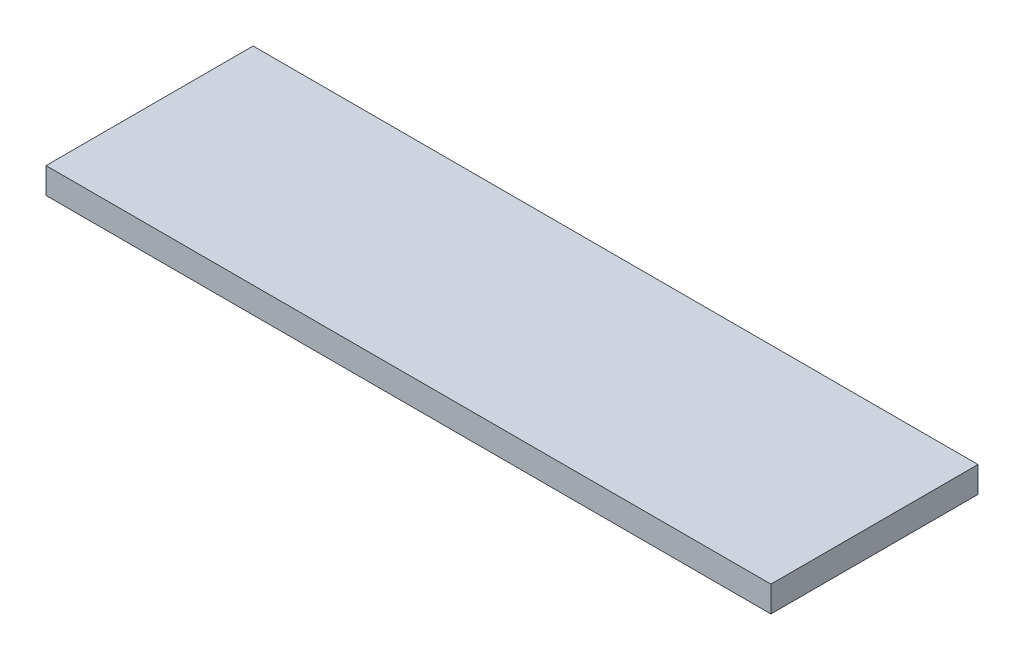
SolidWorks part; units mm, degrees
ref_plane "Front Plane" through (0, 0, 0) normal (0, 0, 1) x (1, 0, 0)
ref_plane "Top Plane" through (0, 0, 0) normal (0, 1, 0) x (1, 0, 0)
ref_plane "Right Plane" through (0, 0, 0) normal (1, 0, 0) x (0, 0, -1)
sketch "Sketch1" plane through (0, 0, 0) normal (0, 1, 0) x (1, 0, 0)
  line L1 (0, 0) -> (88.9, 0)
  line L2 (0, 0) -> (0, 25.4)
  line L3 (0, 25.4) -> (88.9, 25.4)
  line L4 (88.9, 0) -> (88.9, 25.4)
  dimension "D1" = 25.4
  dimension "D2" = 88.9
extrude "Boss-Extrude1" add sketch "Sketch1" along normal blind 3.175
